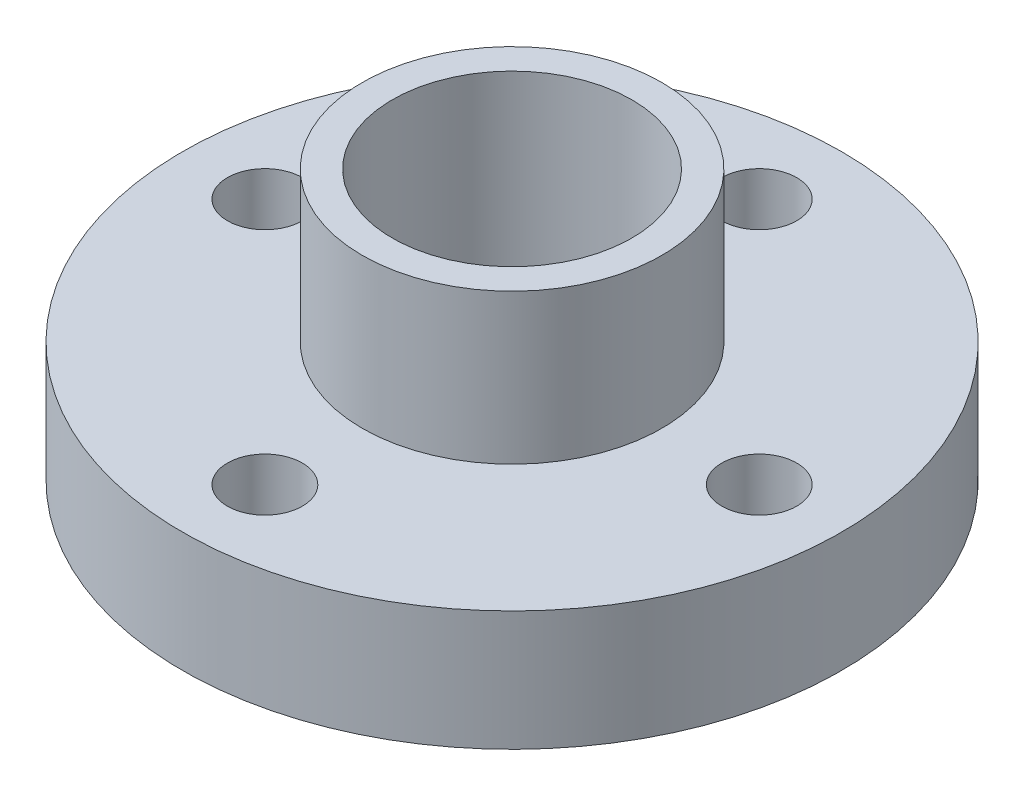
SolidWorks part; units mm, degrees
ref_plane "Front Plane" through (0, 0, 0) normal (0, 0, 1) x (1, 0, 0)
ref_plane "Top Plane" through (0, 0, 0) normal (0, 1, 0) x (1, 0, 0)
ref_plane "Right Plane" through (0, 0, 0) normal (1, 0, 0) x (0, 0, -1)
sketch "Sketch1" plane through (0, 0, 0) normal (0, 0, 1) x (1, 0, 0)
  line L0 (11, 0) -> (11, 4)
  line L1 (11, 4) -> (5, 4)
  line L2 (5, 4) -> (5, 9)
  line L3 (5, 9) -> (4, 9)
  line L4 (4, 9) -> (4, -2)
  line L5 (4, -2) -> (5, -2)
  line L6 (5, -2) -> (5, 0)
  line L7 (5, 0) -> (11, 0)
  line L8 (0, 0) -> (0, 49.7827) construction
  dimension "D1" = 22
  dimension "D2" = 8
  dimension "D3" = 10
  dimension "D4" = 4
  dimension "D5" = 5
  dimension "D6" = 2
revolve "Revolve1" add sketch "Sketch1" angle 360 about L8
sketch "Sketch2" plane through (0, 4, 0) normal (0, 1, 0) x (1, 0, 0)
  circle A0 centre (0, 0) radius 8.25 construction
  point P3 (0, 8.25)
  point P7 (8.25, 0)
  point P8 (0, -8.25)
  point P9 (-8.25, 0)
  point P10 (0, 0)
  point P14 (0, 0)
  dimension "D2" = 16.5
  dimension "D1" = 4
hole_wizard "Tap Drill for M3 Tap1" positions "Sketch3" profile "Sketch4" hole size "M3" standard "ISO" end condition through all
sketch "Sketch3" plane through (0, 4, 0) normal (0, 1, 0) x (1, 0, 0)
  point P0 (0, 8.25)
  point P3 (8.25, 0)
  point P6 (0, -8.25)
  point P9 (-8.25, 0)
sketch "Sketch4" plane through (0, 4, -8.25) normal (1, 0, 0) x (0, 0, 1)
  line L0 (0, 0) -> (0, 6)
  line L1 (0, 6) -> (1.25, 6)
  line L2 (1.25, 6) -> (1.25, 0)
  line L5 (1.25, 0) -> (0, 0)
  line L11 (0, -6.35) -> (0, 107.95) construction
  dimension "Thru Hole Dia." = 2.5
  dimension "Thru Hole Depth" = 6
ref_plane "midplane" through (0, 2, 0) normal (0, 1, 0) x (1, 0, 0)
